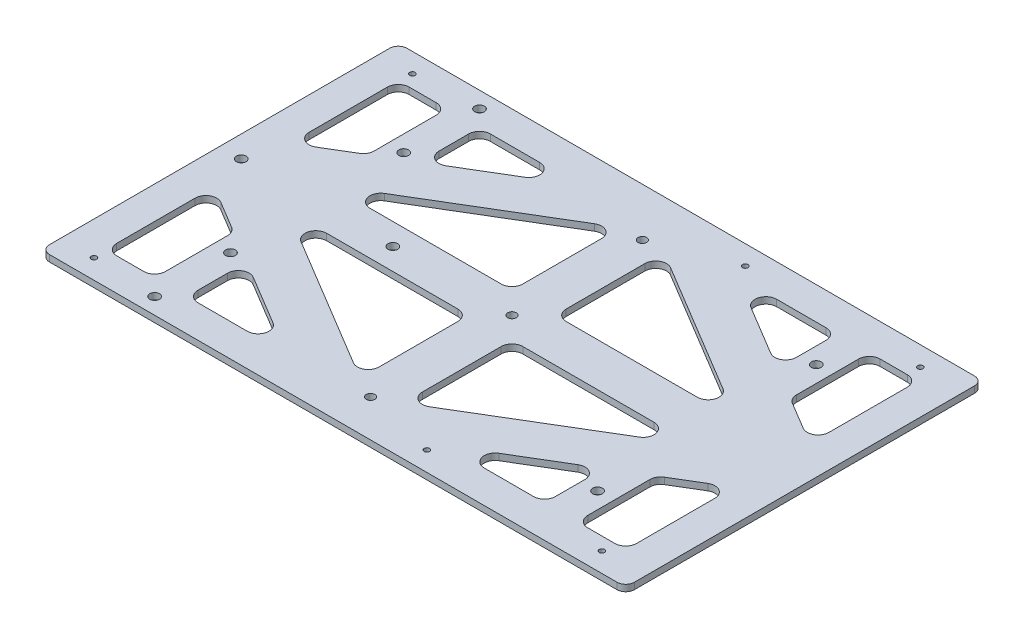
SolidWorks part; units mm, degrees
ref_plane "Alzado" through (0, 0, 0) normal (0, 0, 1) x (1, 0, 0)
ref_plane "Planta" through (0, 0, 0) normal (0, 1, 0) x (1, 0, 0)
ref_plane "Vista lateral" through (0, 0, 0) normal (1, 0, 0) x (0, 0, -1)
sketch "Croquis1" plane through (0, 0, 0) normal (0, 1, 0) x (1, 0, 0)
  line L1 (135, -82.5) -> (-135, -82.5)
  line L2 (135, -82.5) -> (135, 82.5)
  line L3 (135, 82.5) -> (-135, 82.5)
  line L4 (-135, -82.5) -> (-135, 82.5)
  line L5 (135, -82.5) -> (-135, 82.5) construction
  line L6 (135, 82.5) -> (-135, -82.5) construction
  point P0 (0, 0)
  dimension "D1" = 165
  dimension "D2" = 270
extrude "Saliente-Extruir1" add sketch "Croquis1" along normal blind 3
fillet "Redondeo1" radius 4 4 edges at (-135, 1.5, -82.5) (135, 1.5, -82.5) (135, 1.5, 82.5) (-135, 1.5, 82.5)
sketch "Croquis2" plane through (0, 3, 0) normal (0, 1, 0) x (1, 0, 0)
  line L0 (131, 82.5) -> (-131, 82.5) construction
  line L1 (135, -78.5) -> (135, 78.5) construction
  circle A0 centre (90, 50.5) radius 2.25
  dimension "D1" = 4.5
  dimension "D2" = 32
  dimension "D3" = 45
extrude "Cortar-Extruir1" cut sketch "Croquis2" against normal through all
mirror "Simetría1" about plane through (0, 0, 0) normal (0, 0, 1) of "Cortar-Extruir1"
sketch "Croquis3" plane through (0, 3, 0) normal (0, 1, 0) x (1, 0, 0)
  line L0 (-135, 78.5) -> (-135, -78.5) construction
  line L1 (131, 82.5) -> (-131, 82.5) construction
  line L2 (-135, 0) -> (-113.8944, 0) construction
  circle A0 centre (-90, 75) radius 2.25
  circle A1 centre (-90, -75) radius 2.25
  dimension "D1" = 4.5
  dimension "D2" = 45
  dimension "D3" = 7.5
extrude "Cortar-Extruir2" cut sketch "Croquis3" against normal through all
sketch "Croquis4" plane through (0, 3, 0) normal (0, 1, 0) x (1, 0, 0)
  line L0 (0, 82.5) -> (0, -82.5) construction
  line L1 (131, 82.5) -> (-131, 82.5) construction
  line L2 (-131, -82.5) -> (131, -82.5) construction
  line L3 (-135, 0) -> (135, 0) construction
  line L4 (-135, 78.5) -> (-135, -78.5) construction
  line L5 (135, -78.5) -> (135, 78.5) construction
  line L6 (0, -82.5) -> (131, -82.5) construction
  line L7 (135, -82.5) -> (135, 78.5) construction
  line L8 (131, 82.5) -> (0, 82.5) construction
  line L9 (115, 67.5) -> (102.5, 67.5)
  line L12 (110.2817, 0) -> (2.6409, -64.5845) construction
  line L13 (131, 67.5) -> (-131, 67.5) construction
  line L14 (4.9275, 63.2125) -> (110.2817, 0) construction
  line L15 (15, 10) -> (75.5635, 10)
  line L16 (131, 82.5) -> (-131, 82.5) construction
  line L17 (15, -10) -> (75.5635, -10)
  line L18 (10, 51.3381) -> (10, 15)
  line L19 (17.5725, 55.6256) -> (78.136, 19.2875)
  line L20 (78.136, -19.2875) -> (17.5725, -55.6256)
  line L24 (52.1339, 58.2125) -> (74.9275, 44.5363)
  line L29 (15.2174, 80.3624) -> (149.1548, 0) construction
  line L30 (90, 50.5) -> (90, 67.5) construction
  line L31 (149.1548, 0) -> (12.9308, -81.7344) construction
  line L32 (99.9275, 29.5363) -> (112.4275, 22.0363)
  line L34 (82.5, 62.5) -> (82.5, 48.8238)
  line L36 (97.5, 62.5) -> (97.5, 33.8238)
  line L37 (120, 26.3238) -> (120, 62.5)
  line L38 (77.5, 67.5) -> (54.7063, 67.5)
  line L39 (10, -15) -> (10, -51.3381)
  arc A3 (120, 62.5) -> (115, 67.5) centre (115, 62.5) ccw
  arc A4 (120, 26.3238) -> (112.4275, 22.0363) centre (115, 26.3238) cw
  arc A5 (99.9275, 29.5363) -> (97.5, 33.8238) centre (102.5, 33.8238) cw
  arc A6 (102.5, 67.5) -> (97.5, 62.5) centre (102.5, 62.5) ccw
  arc A7 (10, -51.3381) -> (17.5725, -55.6256) centre (15, -51.3381) ccw
  arc A9 (10, 51.3381) -> (17.5725, 55.6256) centre (15, 51.3381) cw
  arc A10 (75.5635, 10) -> (78.136, 19.2875) centre (75.5635, 15) ccw
  arc A11 (75.5635, -10) -> (78.136, -19.2875) centre (75.5635, -15) cw
  arc A12 (15, 10) -> (10, 15) centre (15, 15) cw
  arc A13 (15, -10) -> (10, -15) centre (15, -15) ccw
  arc A14 (82.5, 48.8238) -> (74.9275, 44.5363) centre (77.5, 48.8238) cw
  arc A15 (77.5, 67.5) -> (82.5, 62.5) centre (77.5, 62.5) cw
  arc A16 (52.1339, 58.2125) -> (54.7063, 67.5) centre (54.7063, 62.5) cw
  point P44 (97.5, 30.9929)
  point P64 (10, -10)
  dimension "D5" = 33.6762
  dimension "D6" = 5
  dimension "D7" = 5
  dimension "D13" = 5
  dimension "D14" = 5
  dimension "D15" = 5
  dimension "D16" = 22.0363
  dimension "D2" = 5
  dimension "D4" = 15
  dimension "D8" = 15
  dimension "D10" = 10
  dimension "D11" = 10
  dimension "D12" = 10
  dimension "D3" = 20
  dimension "D1" = 15
extrude "Cortar-Extruir3" cut sketch "Croquis4" against normal through all
mirror "Simetría4" about plane through (0, 0, 0) normal (1, 0, 0) of "Cortar-Extruir3"
sketch "Croquis5" plane through (0, 3, 0) normal (0, 1, 0) x (1, 0, 0)
  line L0 (135, -78.5) -> (135, 78.5) construction
  line L1 (-131, -82.5) -> (131, -82.5) construction
  line L2 (131, 82.5) -> (-131, 82.5) construction
  circle A0 centre (-119.5, 73.5) radius 1.75
  circle A1 centre (34.2, 73.5) radius 1.75
  circle A2 centre (115, 73.5) radius 1.75
  circle A3 centre (115, -73.5) radius 1.75
  circle A4 centre (34.2, -73.5) radius 1.75
  circle A5 centre (-119.5, -73.5) radius 1.75
  point P0 (-119.5, 73.5)
  point P3 (34.2, 73.5)
  point P6 (115, 73.5)
  point P9 (115, -73.5)
  point P12 (34.2, -73.5)
  point P15 (-119.5, -73.5)
  dimension "D1" = 20
  dimension "D2" = 80.8
  dimension "D3" = 153.7
  dimension "D4" = 9
  dimension "D5" = 9
hole_wizard "Taladro roscado M31" positions "Croquis5" profile "Croquis6" tap size "M3" standard "ISO"
sketch "Croquis6" plane through (-119.5, 3, -73.5) normal (1, 0, 0) x (0, 0, 1)
  line L0 (0, 0) -> (0, 9.2511)
  line L1 (0, 9.2511) -> (1.25, 8.5)
  line L2 (1.25, 8.5) -> (1.25, 0)
  line L5 (1.25, 0) -> (0, 0)
  line L10 (0, 9.2511) -> (-1.25, 8.5) construction
  line L11 (0, -6.35) -> (0, 107.95) construction
  dimension "Diámetro de perforador para roscar" = 2.5
  dimension "Profundidad de perforador para roscar" = 8.5
  dimension "Ángulo de perforador" = 118
cosmetic thread "Rosca de taladro1" parameters "D1"=6, "D2"=3
cosmetic thread "Rosca de taladro2" parameters "D1"=6, "D2"=3
cosmetic thread "Rosca de taladro3" parameters "D1"=6, "D2"=3
cosmetic thread "Rosca de taladro4" parameters "D1"=6, "D2"=3
cosmetic thread "Rosca de taladro5" parameters "D1"=6, "D2"=3
cosmetic thread "Rosca de taladro6" parameters "D1"=6, "D2"=3
mirror "Simetría5" about plane through (0, 0, 0) normal (0, 0, 1) of "Cortar-Extruir3"
mirror "Simetría7" about plane through (0, 0, 0) normal (1, 0, 0) of "Simetría5"
mirror "Simetría8" about plane through (0, 0, 0) normal (1, 0, 0) of "Simetría5"
sketch "Croquis9" plane through (0, 3, 0) normal (0, 1, 0) x (1, 0, 0)
  line L0 (-131, -82.5) -> (131, -82.5) construction
  line L1 (-97.5, -62.5) -> (-97.5, -33.8238) construction
  line L2 (-135, 78.5) -> (-135, -78.5) construction
  line L3 (-75.5635, -10) -> (-15, -10) construction
  line L4 (131, 82.5) -> (-131, 82.5) construction
  circle A0 centre (-125, 0) radius 2.25
  circle A1 centre (-90, 40) radius 2.25
  circle A2 centre (-55, 0) radius 2.25
  circle A3 centre (-90, -40) radius 2.25
  point P1 (-90, -40)
  point P3 (-55, 0)
  dimension "D1" = 4.5
  dimension "D5" = 10
  dimension "D2" = 42.5
  dimension "D3" = 7.5
  dimension "D4" = 80
  dimension "D6" = 10
  dimension "D7" = 42.5
extrude "Cortar-Extruir4" cut sketch "Croquis9" against normal blind 4
sketch "Croquis10" plane through (0, 3, 0) normal (0, 1, 0) x (1, 0, 0)
  circle A0 centre (0, 0) radius 2
  circle A1 centre (0, 60.1959) radius 2
  circle A2 centre (0, -65.3126) radius 2
  dimension "D1" = 4
extrude "Cortar-Extruir5" cut sketch "Croquis10" against normal through all
